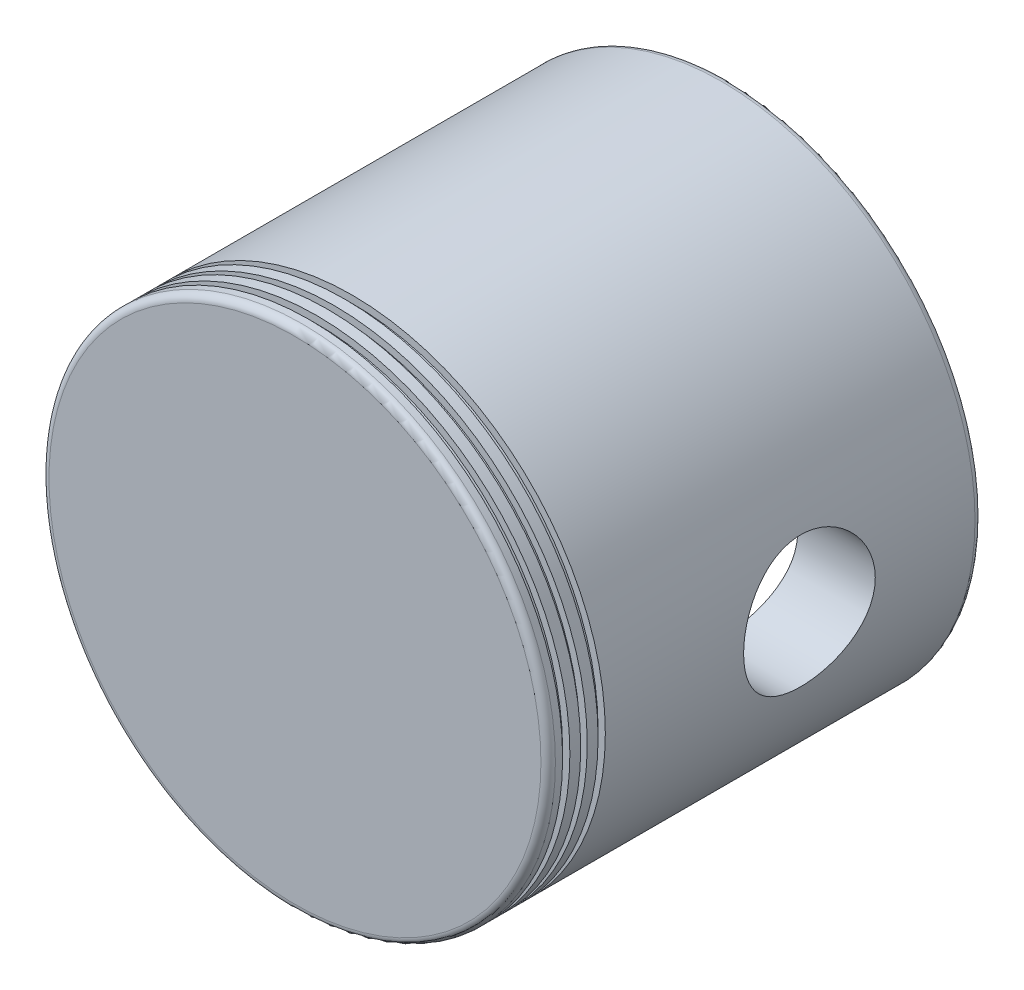
SolidWorks part; units mm, degrees
ref_plane "Front Plane" through (0, 0, 0) normal (0, 0, 1) x (1, 0, 0)
ref_plane "Top Plane" through (0, 0, 0) normal (0, 1, 0) x (1, 0, 0)
ref_plane "Right Plane" through (0, 0, 0) normal (1, 0, 0) x (0, 0, -1)
sketch "Sketch1" plane through (0, 0, 0) normal (1, 0, 0) x (0, 0, -1)
  line L0 (0, 0) -> (83.9466, 0) construction
  line L1 (0, 0) -> (0, 34)
  line L2 (1, 35) -> (2, 35)
  line L3 (60, 34) -> (60, 33.5555)
  line L4 (10.131, 29.8143) -> (10.131, 0)
  line L5 (23.6159, 29.8143) -> (23.6159, 25.2568)
  line L6 (24.6159, 24.2568) -> (47.6159, 24.2568)
  line L7 (11.131, 30.8143) -> (22.6159, 30.8143)
  line L8 (48.6159, 25.2568) -> (48.6159, 29.8143)
  line L9 (59.5284, 32.7065) -> (56.7308, 30.9653)
  line L10 (49.6159, 30.8143) -> (56.2024, 30.8143)
  line L11 (2, 35) -> (2, 34)
  line L12 (2, 34) -> (3, 34)
  line L13 (3, 34) -> (3, 35)
  line L14 (4.5, 35) -> (4.5, 34)
  line L15 (4.5, 34) -> (5.4005, 34)
  line L16 (5.4005, 34) -> (5.4005, 35)
  line L18 (6.9005, 35) -> (6.9005, 34)
  line L19 (6.9005, 34) -> (7.9005, 34)
  line L20 (7.9005, 34) -> (7.9005, 35)
  line L21 (3, 35) -> (4.5, 35)
  line L22 (5.4005, 35) -> (6.9005, 35)
  line L23 (7.9005, 35) -> (59, 35)
  arc A0 (49.6159, 30.8143) -> (48.6159, 29.8143) centre (49.6159, 29.8143) ccw
  arc A1 (22.6159, 30.8143) -> (23.6159, 29.8143) centre (22.6159, 29.8143) cw
  arc A2 (11.131, 30.8143) -> (10.131, 29.8143) centre (11.131, 29.8143) ccw
  arc A3 (23.6159, 25.2568) -> (24.6159, 24.2568) centre (24.6159, 25.2568) ccw
  arc A4 (59, 35) -> (60, 34) centre (59, 34) cw
  arc A5 (0, 34) -> (1, 35) centre (1, 34) cw
  arc A6 (47.6159, 24.2568) -> (48.6159, 25.2568) centre (47.6159, 25.2568) ccw
  arc A7 (56.2024, 30.8143) -> (56.7308, 30.9653) centre (56.2024, 31.8143) ccw
  arc A8 (60, 33.5555) -> (59.5284, 32.7065) centre (59, 33.5555) cw
  point P29 (23.6159, 30.8143)
  dimension "D1" = 1
  dimension "D2" = 1
revolve "Revolve1" add sketch "Sketch1" angle 360 about L0
sketch "Sketch2" plane through (0, 0, -10.131) normal (0, 0, -1) x (-1, 0, 0)
  line L1 (-28.3817, 12) -> (28.3817, 12)
  line L2 (-28.3817, -12) -> (28.3817, -12)
  circle A0 centre (0, 0) radius 30.8143 construction
  arc A1 (28.3817, 12) -> (-28.3817, 12) centre (0, 0) ccw
  arc A2 (28.3817, -12) -> (-28.3817, -12) centre (0, 0) cw
extrude "Cut-Extrude1" cut sketch "Sketch2" along normal blind 70
sketch "Sketch3" plane through (0, 0, 0) normal (1, 0, 0) x (0, 0, -1)
  circle A0 centre (36.1159, 0) radius 9.1
extrude "Cut-Extrude2" cut sketch "Sketch3" against normal mid plane 100
